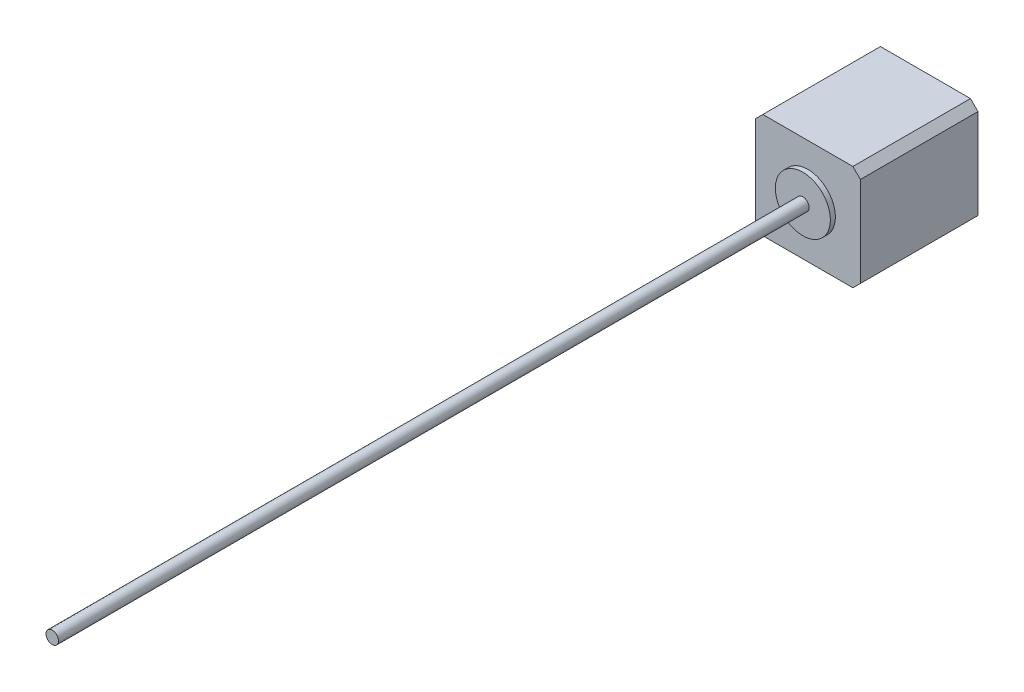
SolidWorks part; units mm, degrees
ref_plane "前视基准面" through (0, 0, 0) normal (0, 0, 1) x (1, 0, 0)
ref_plane "上视基准面" through (0, 0, 0) normal (0, 1, 0) x (1, 0, 0)
ref_plane "右视基准面" through (0, 0, 0) normal (1, 0, 0) x (0, 0, -1)
sketch "草图1" plane through (0, 0, 0) normal (0, 0, 1) x (1, 0, 0)
  line L1 (0, 0) -> (-42, 0)
  line L2 (0, 0) -> (0, 42)
  line L3 (0, 42) -> (-42, 42)
  line L4 (-42, 0) -> (-42, 42)
  dimension "D1" = 42
  dimension "D2" = 42
extrude "凸台-拉伸1" add sketch "草图1" along normal blind 47
chamfer "倒角1" distance 3 angle 45 4 edges at (-42, 0, 23.5) (0, 0, 23.5) (-42, 42, 23.5) (0, 42, 23.5)
sketch "草图2" plane through (0, 0, 47) normal (0, 0, 1) x (1, 0, 0)
  line L0 (-21, 42) -> (-21, 0) construction
  line L1 (-3, 42) -> (-39, 42) construction
  line L2 (-39, 0) -> (-3, 0) construction
  line L3 (-42, 21) -> (-21, 21) construction
  line L4 (-42, 39) -> (-42, 3) construction
  circle A0 centre (-21, 21) radius 11
  dimension "D1" = 22
extrude "凸台-拉伸2" add sketch "草图2" along normal blind 2
sketch "草图3" plane through (0, 0, 49) normal (0, 0, 1) x (1, 0, 0)
  circle A0 centre (-21, 21) radius 2.5
  dimension "D1" = 5
extrude "凸台-拉伸3" add sketch "草图3" along normal blind 300
